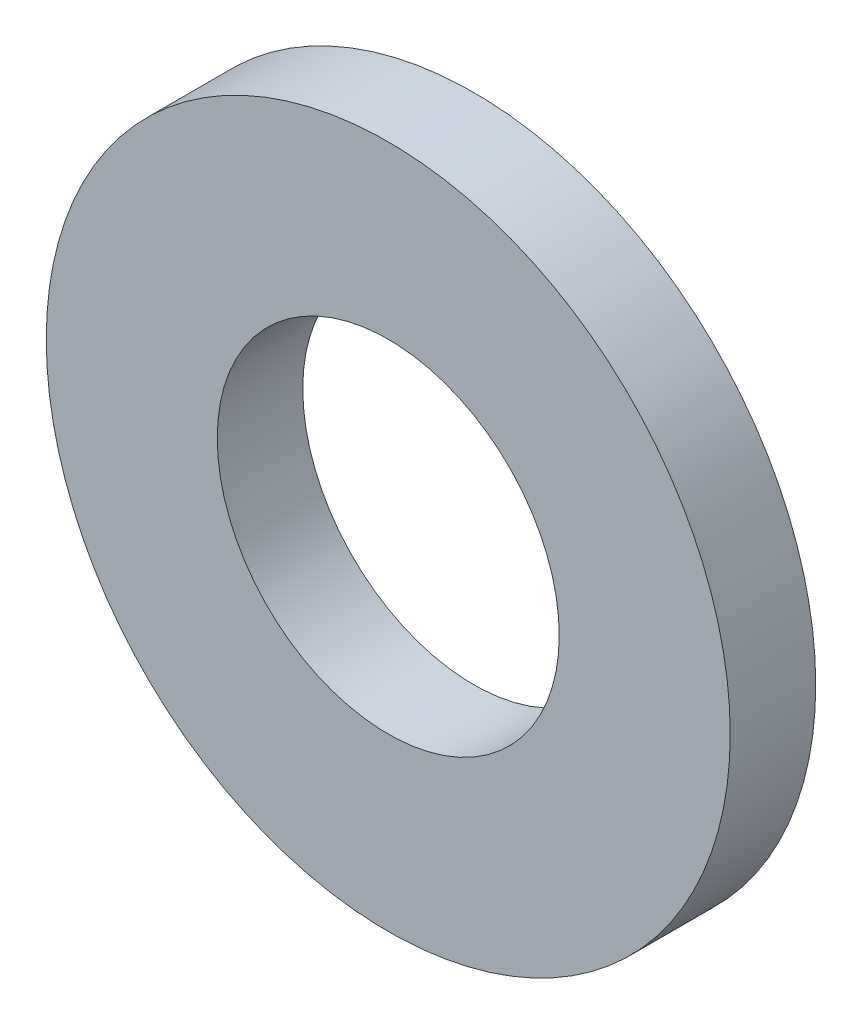
SolidWorks part; units mm, degrees
ref_plane "前视基准面" through (0, 0, 0) normal (0, 0, 1) x (1, 0, 0)
ref_plane "上视基准面" through (0, 0, 0) normal (0, 1, 0) x (1, 0, 0)
ref_plane "右视基准面" through (0, 0, 0) normal (1, 0, 0) x (0, 0, -1)
sketch "草图1" plane through (0, 0, 0) normal (0, 0, 1) x (1, 0, 0)
  circle A0 centre (0, 0) radius 6
  circle A1 centre (0, 0) radius 3
  dimension "D1" = 6
  dimension "D2" = 12
extrude "凸台-拉伸1" add sketch "草图1" along normal blind 1.5
